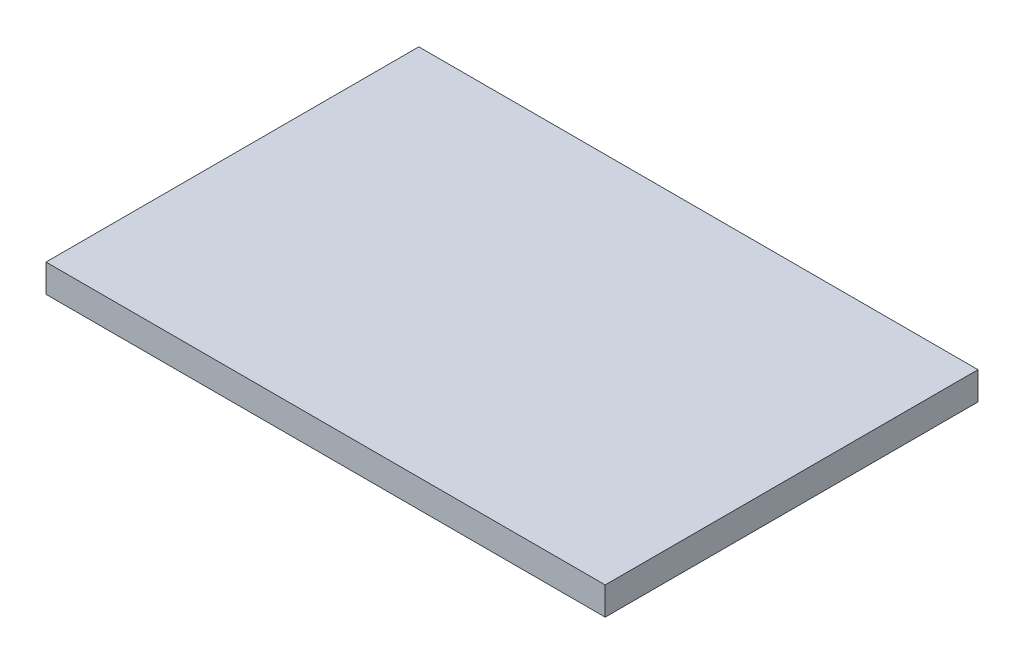
SolidWorks part; units mm, degrees
ref_plane "Front Plane" through (0, 0, 0) normal (0, 0, 1) x (1, 0, 0)
ref_plane "Top Plane" through (0, 0, 0) normal (0, 1, 0) x (1, 0, 0)
ref_plane "Right Plane" through (0, 0, 0) normal (1, 0, 0) x (0, 0, -1)
sketch "Sketch1" plane through (0, 0, 0) normal (0, 1, 0) x (1, 0, 0)
  line L1 (-15, 10) -> (15, 10)
  line L2 (-15, 10) -> (-15, -10)
  line L3 (-15, -10) -> (15, -10)
  line L4 (15, 10) -> (15, -10)
  line L5 (-15, 10) -> (15, -10) construction
  line L6 (-15, -10) -> (15, 10) construction
  point P0 (0, 0)
  dimension "D1" = 30
  dimension "D2" = 20
extrude "Boss-Extrude1" add sketch "Sketch1" along normal blind 1.5
